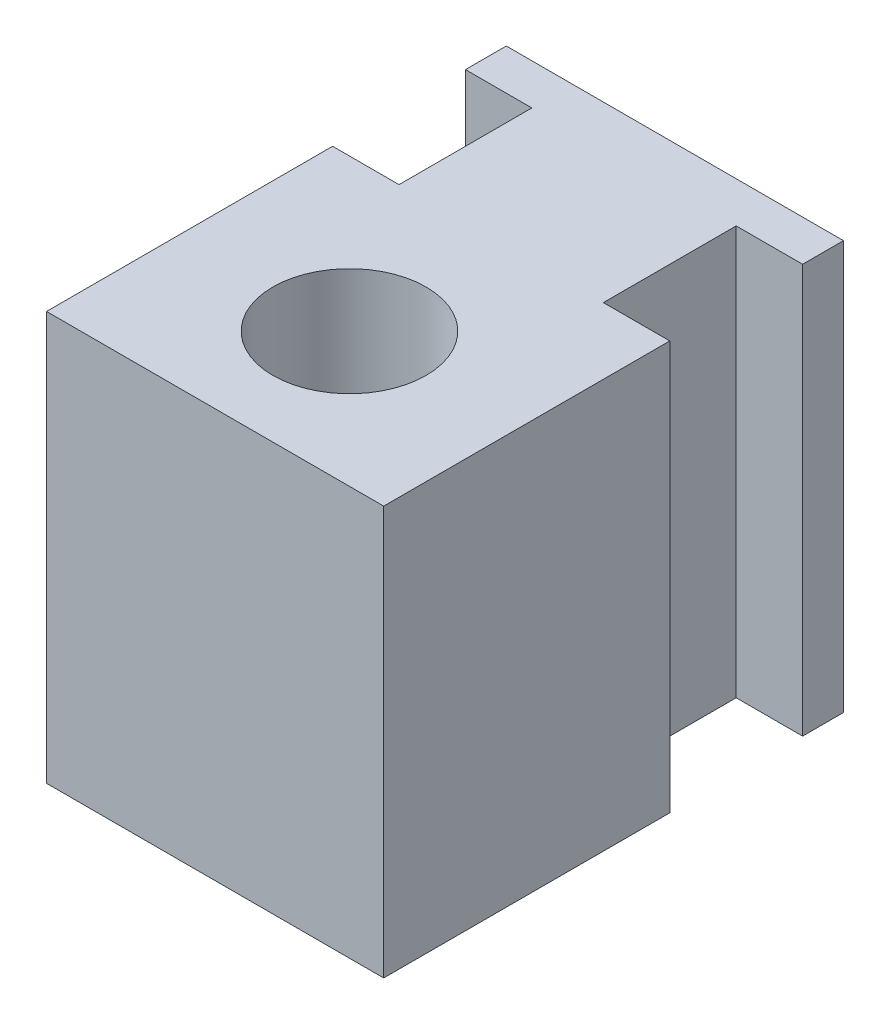
SolidWorks part; units mm, degrees
material "ASTM A36 Aço"
ref_plane "Plano frontal" through (0, 0, 0) normal (0, 0, 1) x (1, 0, 0)
ref_plane "Plano superior" through (0, 0, 0) normal (0, 1, 0) x (1, 0, 0)
ref_plane "Plano direito" through (0, 0, 0) normal (1, 0, 0) x (0, 0, -1)
sketch "Esboço1" plane through (0, 0, 0) normal (0, 1, 0) x (1, 0, 0)
  line L1 (-16.5, 0) -> (16.5, 0)
  line L2 (-16.5, 0) -> (-16.5, 45)
  line L3 (-16.5, 45) -> (16.5, 45)
  line L4 (16.5, 0) -> (16.5, 45)
  point P4 (0, 0)
  dimension "D1" = 33
  dimension "D2" = 45
extrude "Ressalto-extrusão1" add sketch "Esboço1" along normal mid plane 40
sketch "Esboço2" plane through (0, 20, 0) normal (0, 1, 0) x (1, 0, 0)
  line L0 (16.5, 45) -> (-16.5, 45) construction
  point P0 (0, 13.15)
  dimension "D1" = 31.85
hole_wizard "Furo de diâmetro Ø15.0 (15)1" positions "Esboço2" profile "Esboço3" hole size "Ø15.0" standard "Ansi Metric" end condition through all
sketch "Esboço3" plane through (0, 20, -13.15) normal (1, 0, 0) x (0, 0, 1)
  line L0 (0, 0) -> (0, 40)
  line L1 (0, 40) -> (7.5, 40)
  line L2 (7.5, 40) -> (7.5, 0)
  line L5 (7.5, 0) -> (0, 0)
  line L11 (0, -6.35) -> (0, 107.95) construction
  dimension "Thru Hole Dia." = 15
  dimension "Thru Hole Depth" = 40
sketch "Esboço4" plane through (0, 0, -45) normal (0, 0, -1) x (-1, 0, 0)
  point P0 (0, 0)
hole_wizard "Furo roscado de M10x1.51" positions "Esboço4" profile "Esboço5" tap size "M10x1.5" standard "Ansi Metric"
sketch "Esboço5" plane through (0, 0, -45) normal (1, 0, 0) x (0, 1, 0)
  line L0 (0, 0) -> (0, 20)
  line L1 (0, 20) -> (4.25, 17.4463)
  line L2 (4.25, 17.4463) -> (4.25, 0)
  line L5 (4.25, 0) -> (0, 0)
  line L10 (0, 20) -> (-4.25, 17.4463) construction
  line L11 (0, -6.35) -> (0, 107.95) construction
  dimension "Tap Drill Dia." = 8.5
  dimension "Tap Drill Depth" = 20
  dimension "Drill Angle" = 118
cosmetic thread "Rosca de furo2" parameters "D1"=18, "D2"=10
sketch "Esboço6" plane through (0, 20, 0) normal (0, 1, 0) x (1, 0, 0)
  line L0 (-16.5, 45) -> (-16.5, 0) construction
  line L1 (-16.5, 41) -> (-10, 41)
  line L2 (-16.5, 41) -> (-16.5, 28)
  line L3 (-16.5, 28) -> (-10, 28)
  line L4 (-10, 41) -> (-10, 28)
  line L5 (16.5, 0) -> (16.5, 45) construction
  line L6 (16.5, 41) -> (10, 41)
  line L7 (16.5, 41) -> (16.5, 28)
  line L8 (16.5, 28) -> (10, 28)
  line L9 (10, 41) -> (10, 28)
  line L10 (16.5, 45) -> (-16.5, 45) construction
  dimension "D1" = 13
  dimension "D2" = 4
  dimension "D3" = 20
extrude "Corte-extrusão1" cut sketch "Esboço6" against normal through all
